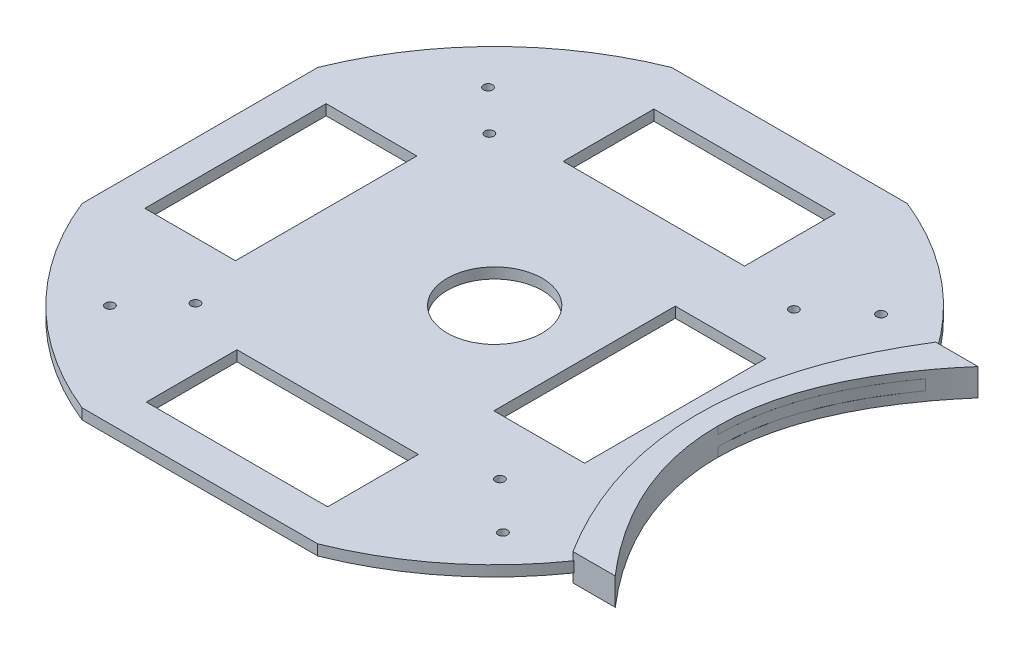
SolidWorks part; units mm, degrees
ref_plane "Front Plane" through (0, 0, 0) normal (0, 0, 1) x (1, 0, 0)
ref_plane "Top Plane" through (0, 0, 0) normal (0, 1, 0) x (1, 0, 0)
ref_plane "Right Plane" through (0, 0, 0) normal (1, 0, 0) x (0, 0, -1)
sketch "Sketch1" plane through (0, 0, 0) normal (0, 1, 0) x (1, 0, 0)
  line L1 (-97.5, -97.5) -> (97.5, -97.5)
  line L2 (-97.5, -97.5) -> (-97.5, 97.5)
  line L3 (-97.5, 97.5) -> (97.5, 97.5)
  line L4 (97.5, -97.5) -> (97.5, 97.5)
  line L5 (-97.5, -97.5) -> (97.5, 97.5) construction
  line L6 (-97.5, 97.5) -> (97.5, -97.5) construction
  point P0 (0, 0)
  dimension "D1" = 195
  dimension "D2" = 195
sketch "Sketch2" plane through (0, 0, 0) normal (0, 1, 0) x (1, 0, 0)
  line L0 (-97.5, -97.5) -> (97.5, 97.5) construction
  circle A0 centre (0, 0) radius 105
  circle A1 centre (0, 0) radius 177.8364
  dimension "D1" = 210
extrude "Boss-Extrude3" add sketch "Sketch1" along normal blind 3.5
extrude "Cut-Extrude2" cut sketch "Sketch2" along normal blind 30
sketch "Sketch4" plane through (0, 0, 0) normal (0, 1, 0) x (1, 0, 0)
  line L0 (30, -30.2592) -> (30, 29.7408)
  line L1 (0, 0) -> (0, -97.5) construction
  line L2 (30, -30.2592) -> (60, -30.2592)
  line L3 (0, 0) -> (0, 114.59) construction
  line L4 (-38.9711, -97.5) -> (38.9711, -97.5) construction
  line L5 (0, 0) -> (-44.5, 0) construction
  line L6 (-44.5, 0) -> (-97.5, 0) construction
  line L7 (-97.5, 38.9711) -> (-97.5, -38.9711) construction
  line L9 (-30, 52.6693) -> (30, 52.6693)
  line L10 (-30, 52.6693) -> (-30, 82.6693)
  line L11 (-30, 82.6693) -> (30, 82.6693)
  line L12 (30, 52.6693) -> (30, 82.6693)
  line L13 (-30, 52.6693) -> (30, 82.6693) construction
  line L14 (-30, 82.6693) -> (30, 52.6693) construction
  line L15 (-85.7442, -30) -> (-55.7442, -30)
  line L16 (-85.7442, -30) -> (-85.7442, 30)
  line L17 (-85.7442, 30) -> (-55.7442, 30)
  line L18 (-55.7442, -30) -> (-55.7442, 30)
  line L19 (-85.7442, -30) -> (-55.7442, 30) construction
  line L20 (-85.7442, 30) -> (-55.7442, -30) construction
  line L21 (-30, 52.6693) -> (-30, -55.2454) construction
  line L22 (-30, -85.2454) -> (30, -85.2454)
  line L23 (-30, -85.2454) -> (-30, -55.2454)
  line L24 (-30, -55.2454) -> (30, -55.2454)
  line L25 (30, -85.2454) -> (30, -55.2454)
  line L26 (-30, -85.2454) -> (30, -55.2454) construction
  line L27 (-30, -55.2454) -> (30, -85.2454) construction
  line L28 (-30, -55.2454) -> (-29.9439, -56.6452) construction
  line L29 (30, 52.6693) -> (30, -55.2454) construction
  line L30 (30, -55.2454) -> (30.8587, -54.4354) construction
  line L31 (-55.7442, -30) -> (85.9303, -30) construction
  line L32 (85.9303, -30) -> (85.9303, 30) construction
  line L33 (85.9303, 30) -> (-55.7442, 30) construction
  line L34 (30, 29.7408) -> (60, 29.7408)
  line L35 (60, -30.2592) -> (60, 29.7408)
  point P3 (-70.7442, 0)
  point P5 (0, 67.6693)
  point P6 (0, -70.2454)
  dimension "D2" = 30
  dimension "D3" = 30
  dimension "D4" = 60
  dimension "D5" = 60
  dimension "D6" = 30
  dimension "D7" = 53
  dimension "D8" = 90
  dimension "D9" = 30
  dimension "D10" = 60
  dimension "D11" = 60
extrude "Cut-Extrude7" cut sketch "Sketch4" along normal blind 5
sketch "Sketch6" plane through (0, 0, 0) normal (0, 1, 0) x (1, 0, 0)
  line L0 (97.5, 0) -> (97.5, -60) construction
  line L1 (97.5, -38.9711) -> (97.5, 38.9711) construction
  line L2 (99.8878, 60) -> (85.8878, 60)
  line L3 (97.5, 0) -> (97.5, 60) construction
  line L4 (97.5, 60) -> (99.8878, 60) construction
  line L5 (99.8878, 60) -> (99.8878, -60) construction
  line L6 (99.8878, -60) -> (97.5, -60) construction
  line L7 (99.8878, -60) -> (85.8878, -60)
  spline S0 degree 2 poles (99.8878, 60) (47.8636, 0) (99.8878, -60) knots 0 0 0 1 1 1
  spline S1 degree 2 poles (85.8878, 60) (48.4396, 0) (85.8878, -60) knots 0 0 0 1 1 1
  dimension "D1" = 60
  dimension "D2" = 60
  dimension "D3" = 14
  dimension "D4" = 14
extrude "Boss-Extrude5" add sketch "Sketch6" along normal blind 6 and the other way blind 3
sketch "Sketch11" plane through (0, 0, 0) normal (0, 1, 0) x (1, 0, 0)
  line L0 (97.5, 0) -> (97.5, -60) construction
  line L2 (99.8878, -60) -> (114.5775, -60)
  line L3 (97.5, 0) -> (97.5, 59.9868) construction
  line L4 (97.5, 59.9868) -> (99.8878, 59.9868) construction
  line L5 (99.8878, 59.9868) -> (99.8878, -60) construction
  line L6 (99.8878, -60) -> (97.5, -60) construction
  line L7 (114.5775, -60) -> (112.4692, 59.9868)
  line L8 (112.4692, 59.9868) -> (99.8878, 59.9868)
  spline S0 degree 2 poles (99.8878, 59.9868) (47.8636, -0.0045) (99.8878, -60) knots 0 0 0 1 1 1
  dimension "D1" = 60
extrude "Cut-Extrude12" cut sketch "Sketch11" against normal blind 6 and the other way blind 6
sketch "Sketch13" plane through (0, 0, 0) normal (0, 1, 0) x (1, 0, 0)
  line L0 (-63.643, 61.4638) -> (66.357, 61.4638) construction
  line L1 (-63.643, 61.4638) -> (-63.643, -63.6362) construction
  line L2 (-63.643, -63.6362) -> (66.357, -63.6362) construction
  line L3 (0, 0) -> (-63.643, -63.6362) construction
  circle A0 centre (-63.643, 61.4638) radius 1.5
  circle A1 centre (66.357, 61.4638) radius 1.5
  circle A2 centre (66.357, -63.6362) radius 1.5
  circle A3 centre (-63.643, -63.6362) radius 1.5
  circle A4 centre (0, 0) radius 15.7219
  dimension "D1" = 3
  dimension "D3" = 3
  dimension "D4" = 3
  dimension "D5" = 3
  dimension "D2" = 130
  dimension "D6" = 125.1
  dimension "D7" = 130
  dimension "D9" = 90
extrude "top to mid stand" cut sketch "Sketch13" along normal blind 6
sketch "Sketch14" plane through (0, 0, 0) normal (0, 1, 0) x (1, 0, 0)
  line L0 (-50.174, 48.4164) -> (50.5569, 48.4164) construction
  line L1 (-50.174, -48.8116) -> (50.5569, 48.4164) construction
  line L2 (-50.174, -48.8116) -> (-50.174, 48.4164) construction
  line L3 (-50.174, 48.4164) -> (50.5569, -48.8116) construction
  circle A0 centre (-50.174, 48.4164) radius 1.5
  circle A1 centre (50.5569, 48.4164) radius 1.5
  circle A2 centre (50.5569, -48.8116) radius 1.5
  circle A3 centre (-50.174, -48.8116) radius 1.5
  dimension "D1" = 3
  dimension "D3" = 3
  dimension "D4" = 3
  dimension "D5" = 3
  dimension "D2" = 140
extrude "mit to bot stand" cut sketch "Sketch14" along normal blind 6
